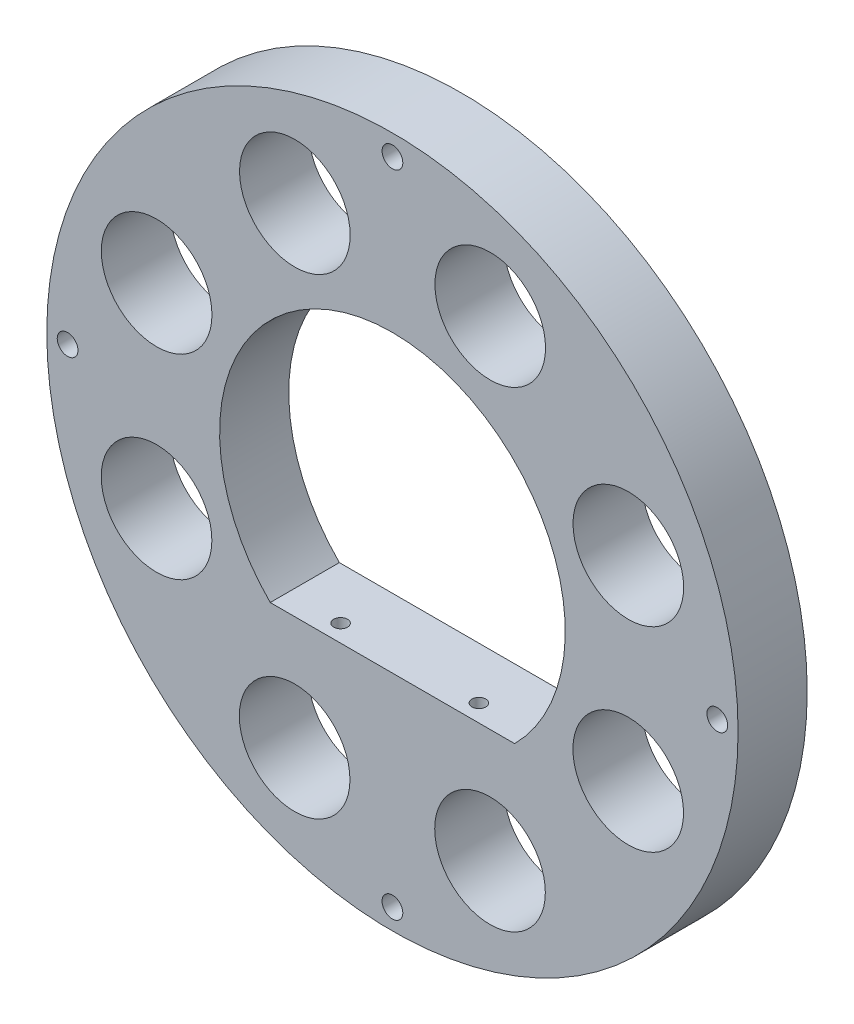
SolidWorks part; units mm, degrees
ref_plane "Front Plane" through (0, 0, 0) normal (0, 0, 1) x (1, 0, 0)
ref_plane "Top Plane" through (0, 0, 0) normal (0, 1, 0) x (1, 0, 0)
ref_plane "Right Plane" through (0, 0, 0) normal (1, 0, 0) x (0, 0, -1)
sketch "Sketch1" plane through (0, 0, 0) normal (0, 0, 1) x (1, 0, 0)
  line L0 (17.6777, -17.6777) -> (-17.6777, -17.6777)
  circle A0 centre (0, 0) radius 50
  arc A2 (17.6777, -17.6777) -> (-17.6777, -17.6777) centre (0, 0) ccw
extrude "Boss-Extrude1" add sketch "Sketch1" along normal blind 10
sketch "Sketch3" plane through (0, 0, 0) normal (0, 0, -1) x (-1, 0, 0)
  circle A0 centre (-14.1464, 34.1095) radius 8
  circle A1 centre (14.1161, 34.122) radius 8
  circle A2 centre (34.1095, 14.1464) radius 8
  circle A3 centre (34.122, -14.1161) radius 8
  circle A4 centre (14.1464, -34.1095) radius 8
  circle A5 centre (-14.1161, -34.122) radius 8
  circle A6 centre (-34.1095, -14.1464) radius 8
  circle A7 centre (-34.122, 14.1161) radius 8
  point P19 (0, 0)
  dimension "D1" = 8
extrude "Cut-Extrude1" cut sketch "Sketch3" against normal blind 20 contours A0 | A1 | A2 | A3 | A4 | A5 | A6 | A7
sketch "Sketch4" plane through (0, 0, 0) normal (0, 0, -1) x (-1, 0, 0)
  circle A1 centre (0, 46.99) radius 1.5
  circle A2 centre (46.99, 0) radius 1.5
  circle A3 centre (0, -46.99) radius 1.5
  circle A4 centre (-46.99, 0) radius 1.5
  point P14 (0, 0)
  dimension "D1" = 4
extrude "Cut-Extrude2" cut sketch "Sketch4" against normal blind 30
sketch "Sketch5" plane through (0, -17.6777, 0) normal (0, 1, 0) x (1, 0, 0)
  line L0 (-17.6777, -10) -> (17.6777, -10) construction
  circle A0 centre (10, -7.5) radius 1
  circle A1 centre (-10, -7.5) radius 1
  point P9 (0, -5)
  dimension "D1" = 20
  dimension "D2" = 2.5
extrude "Cut-Extrude3" cut sketch "Sketch5" against normal blind 10
